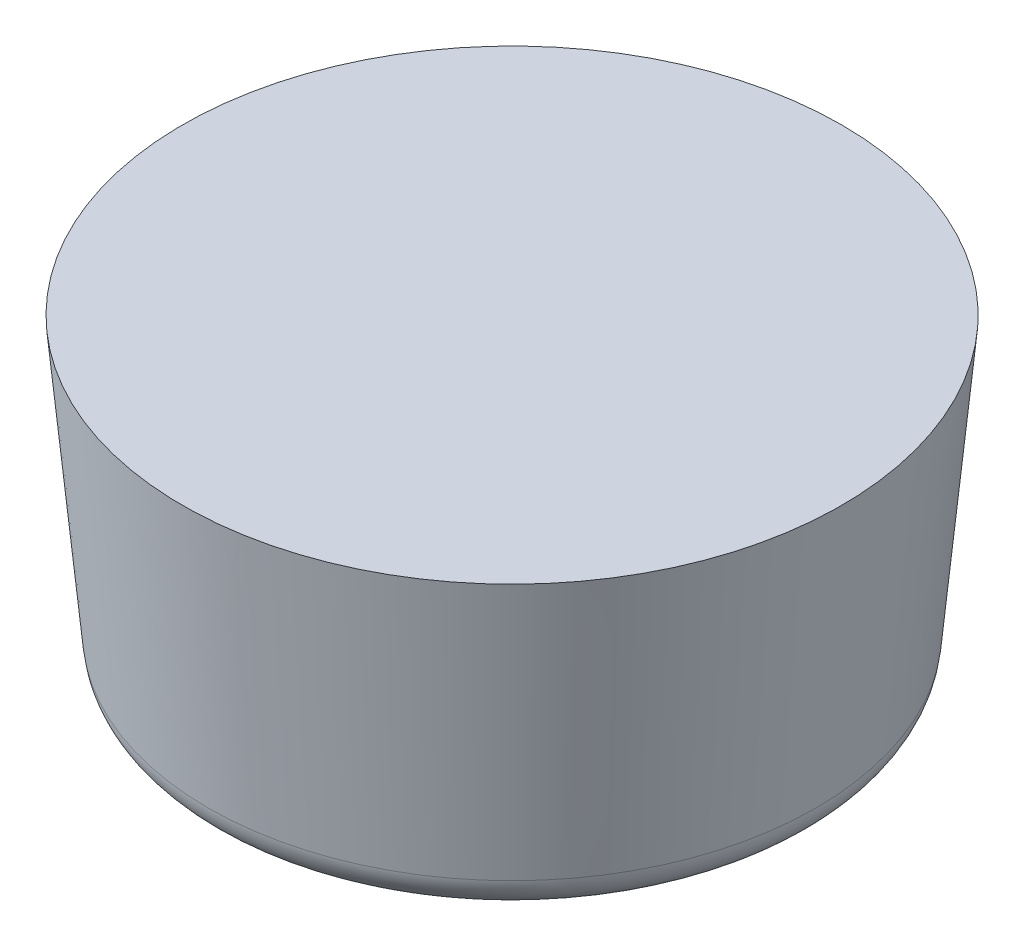
SolidWorks part; units mm, degrees
ref_plane "Alzado" through (0, 0, 0) normal (0, 0, 1) x (1, 0, 0)
ref_plane "Planta" through (0, 0, 0) normal (0, 1, 0) x (1, 0, 0)
ref_plane "Vista lateral" through (0, 0, 0) normal (1, 0, 0) x (0, 0, -1)
sketch "Croquis1" plane through (0, 0, 0) normal (1, 0, 0) x (0, 0, -1)
  line L0 (0, 0) -> (0, 16) construction
  line L1 (0, 16) -> (-17, 16)
  line L2 (-17, 16) -> (-15.5, 0)
  line L3 (-15.5, 0) -> (-7.5, 0)
  line L4 (-7.5, 0) -> (-7.5, 7)
  line L5 (-7.5, 7) -> (-2.5, 7)
  line L6 (-2.5, 7) -> (-2.5, 12)
  line L7 (-2.5, 12) -> (0, 12)
  line L8 (0, 16) -> (0, 12)
  dimension "D1" = 34
  dimension "D2" = 31
  dimension "D3" = 8
  dimension "D4" = 5
  dimension "D5" = 7
  dimension "D6" = 5
  dimension "D7" = 16
revolve "Revolución1" add sketch "Croquis1" angle 360 about L0
fillet "Redondeo1" radius 2 2 edges at (0, 0, -7.5) (0, 0, -15.5)
